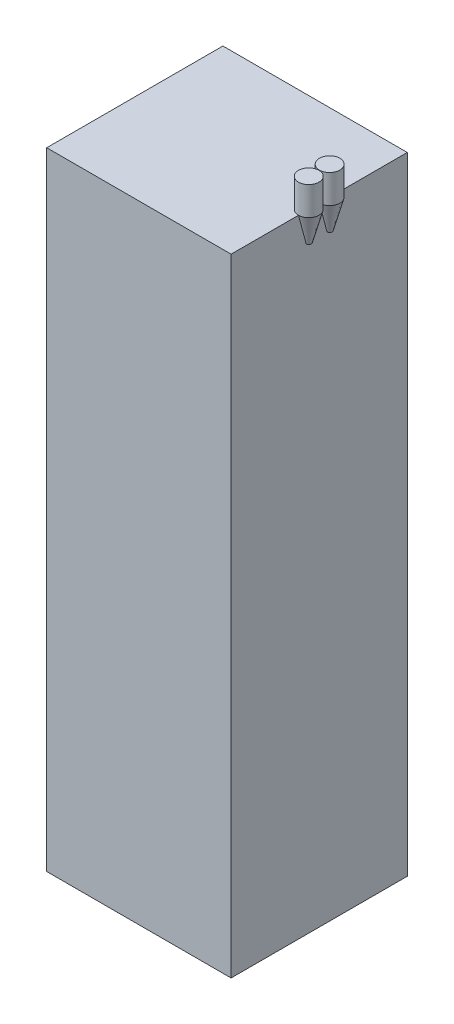
SolidWorks part; units mm, degrees
ref_plane "Front Plane" through (0, 0, 0) normal (0, 0, 1) x (1, 0, 0)
ref_plane "Top Plane" through (0, 0, 0) normal (0, 1, 0) x (1, 0, 0)
ref_plane "Right Plane" through (0, 0, 0) normal (1, 0, 0) x (0, 0, -1)
sketch "Sketch1" plane through (0, 0, 0) normal (0, 1, 0) x (1, 0, 0)
  line L1 (-22.5, -21.5) -> (22.5, -21.5)
  line L2 (-22.5, -21.5) -> (-22.5, 21.5)
  line L3 (-22.5, 21.5) -> (22.5, 21.5)
  line L4 (22.5, -21.5) -> (22.5, 21.5)
  line L5 (-22.5, -21.5) -> (22.5, 21.5) construction
  line L6 (-22.5, 21.5) -> (22.5, -21.5) construction
  point P0 (0, 0)
  dimension "D1" = 45
  dimension "D2" = 43
extrude "Boss-Extrude1" add sketch "Sketch1" along normal blind 153
sketch "Sketch2" plane through (0, 153, 0) normal (0, 1, 0) x (1, 0, 0)
  line L1 (22.5, -21.5) -> (22.5, 21.5) construction
  line L2 (0, 0) -> (5.3365, 0) construction
  circle A0 centre (22.5, -2.55) radius 2.5
  circle A1 centre (22.5, 2.55) radius 2.5
  dimension "D1" = 5
  dimension "D2" = 5.1
extrude "Boss-Extrude4" add sketch "Sketch2" along normal blind 7
sketch "Sketch3" plane through (0, 153, 0) normal (0, -1, 0) x (1, 0, 0)
  line L0 (22.5, 5.05) -> (22.5, 0.05) construction
  line L1 (22.5, -0.05) -> (22.5, -5.05) construction
  circle A0 centre (22.5, 2.55) radius 2.5
  circle A1 centre (22.5, -2.55) radius 2.5
  arc A2 (22.5, 0.05) -> (22.5, 5.05) centre (22.5, 2.55) ccw construction
  arc A3 (22.5, -5.05) -> (22.5, -0.05) centre (22.5, -2.55) ccw construction
extrude "Boss-Extrude5" add sketch "Sketch3" along normal blind 7 draft 15
